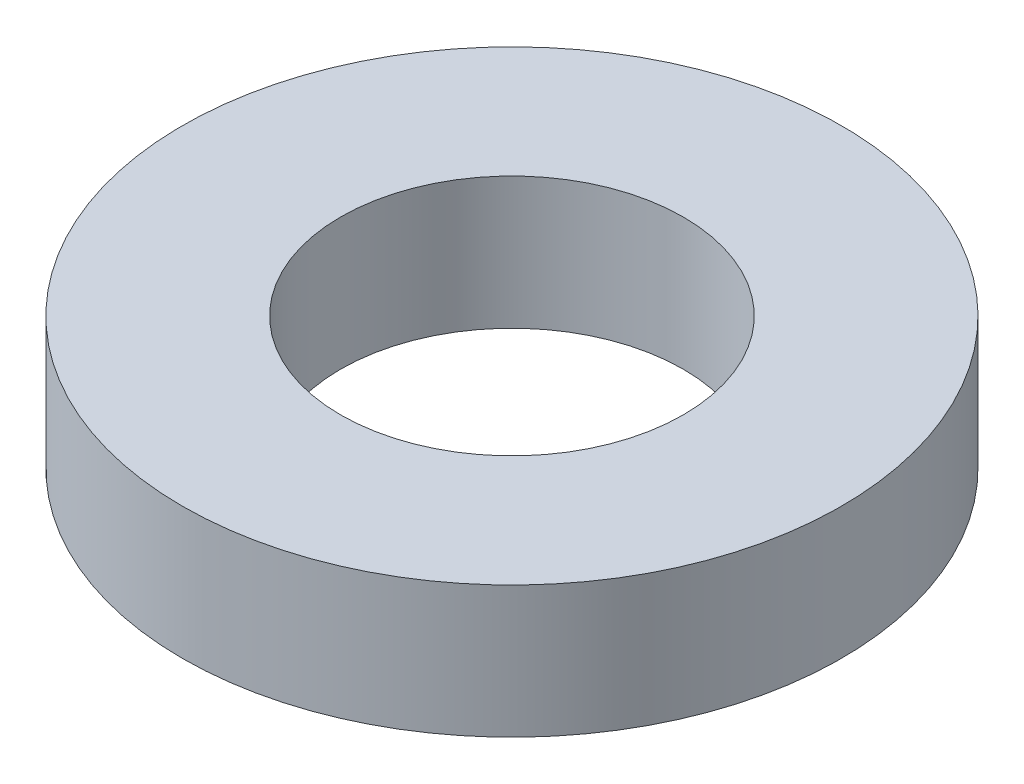
SolidWorks part; units mm, degrees
ref_plane "Front Plane" through (0, 0, 0) normal (0, 0, 1) x (1, 0, 0)
ref_plane "Top Plane" through (0, 0, 0) normal (0, 1, 0) x (1, 0, 0)
ref_plane "Right Plane" through (0, 0, 0) normal (1, 0, 0) x (0, 0, -1)
sketch "Sketch1" plane through (0, 0, 0) normal (0, 1, 0) x (1, 0, 0)
  circle A0 centre (0, 0) radius 1.625
  circle A1 centre (0, 0) radius 3.125
  dimension "D1" = 3.25
  dimension "D2" = 6.25
extrude "Boss-Extrude1" add sketch "Sketch1" along normal blind 1.25
